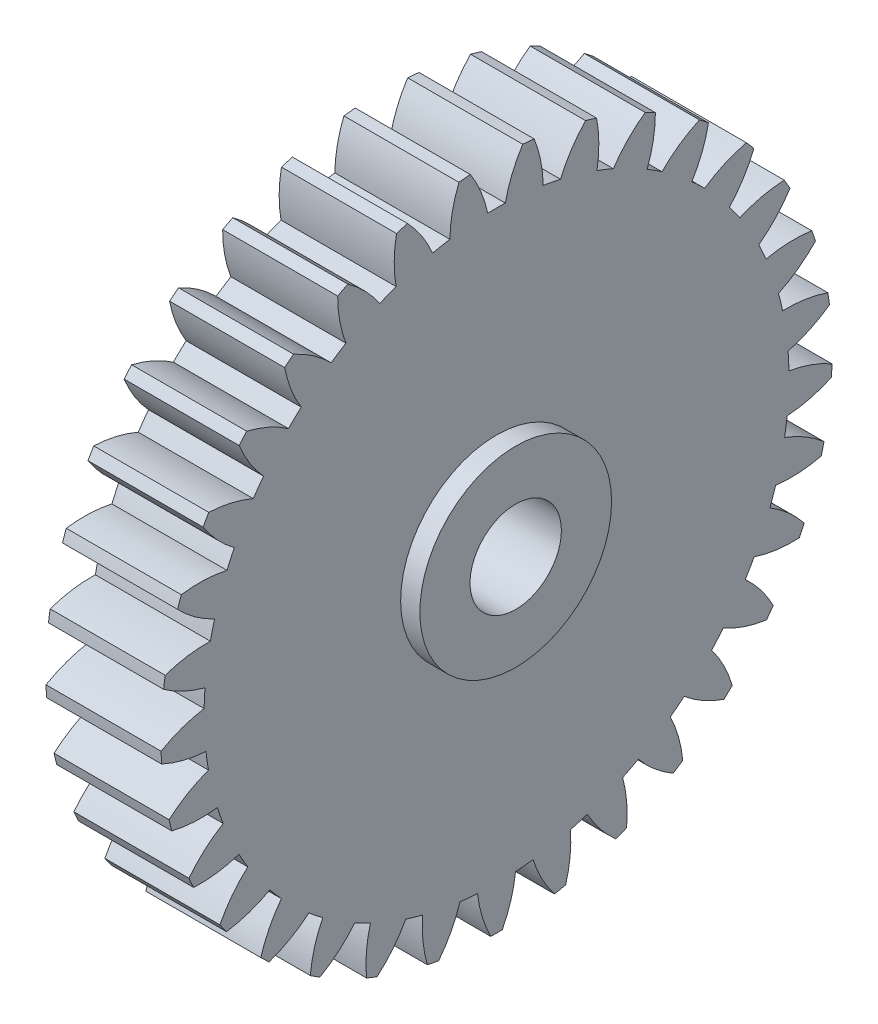
SolidWorks part; units mm, degrees
ref_plane "Plane1" through (0, 0, 0) normal (0, 0, 1) x (1, 0, 0)
ref_plane "Plane2" through (0, 0, 0) normal (0, 1, 0) x (1, 0, 0)
ref_plane "Plane3" through (0, 0, 0) normal (1, 0, 0) x (0, 0, -1)
sketch "HoldingSke" plane through (0, 0, 0) normal (0, 1, 0) x (1, 0, 0)
  line L0 (0, 0) -> (0.8387, -0.5446)
  line L1 (-15, 0) -> (100, 0) construction
  line L2 (0, 0) -> (-2.1039, 2.3779)
  line L3 (0, 0) -> (-11.863, 4.5341)
  line L4 (0, 0) -> (7.2428, 4.7035)
  line L5 (0, 0) -> (-46.8476, -17.4728)
  line L6 (0, 0) -> (-6.6317, -4.4744)
  line L7 (-2.1039, 2.3779) -> (8.6586, 51.2059)
  line L8 (-76.2, 54.61) -> (-74.4, 54.61)
  line L9 (-71.009, 38.7566) -> (-53.1078, 45.2721)
  line L10 (-76.2, 71.12) -> (104.1128, 71.12)
  line L11 (0, 0) -> (-8, 0)
  line L12 (-76.2, 101.6) -> (-76.162, 101.6)
  line L13 (24.9733, 27.94) -> (52.9518, 28.4284)
  line L14 (24.9733, 27.94) -> (24.9743, 27.94)
  line L15 (24.9733, 27.94) -> (100.4006, 29.5858)
  line L16 (-63.627, -1) -> (-12.827, -1)
  circle A0 centre (0, 0) radius 5
  circle A1 centre (0, 0) radius 15.249
  circle A2 centre (0, 0) radius 37.5
  circle A3 centre (0, 0) radius 5
  dimension "MHD" = 30.498
  dimension "Hub_dia" = 75
  dimension "Bore" = 10
  dimension "MBD" = 10
  dimension "Num_teeth" = 33
  dimension "Pitch" = 1
  dimension "Overall_len" = 50
  dimension "Show_teeth" = 33
  dimension "Thickness" = 8
  dimension "OAL" = 50.0001
  dimension "T_dim" = 1.8
  dimension "Ap" = 20
  dimension "H" = 19.05
  dimension "Pitch_radius" = 180.3128
  dimension "Width" = 8
  dimension "Backlash" = 0.038
  dimension "Addendum_fac" = 1
  dimension "Dedendum_fac" = 1.25
  dimension "Clearance_fac" = 0.25
  dimension "Dedendum_add" = 0.001
  dimension "Module" = 1
sketch "BasProSke" plane through (0, 0, 0) normal (0, 1, 0) x (1, 0, 0)
  line L0 (-10, 0) -> (60, 0) construction
  line L1 (0, 0) -> (0, 17.5)
  line L2 (0, 0) -> (6, 0)
  line L3 (6, 0) -> (6, 17.5)
  line L4 (6, 17.5) -> (0, 17.5)
  dimension "Thickness" = 6
  dimension "Diameter" = 35
revolve "Base-Revolve" add sketch "BasProSke" angle 360 about L0
sketch "TooCutSke" plane through (0, 0, 0) normal (1, 0, 0) x (0, 0, -1)
  line L1 (0, 0) -> (0, 107) construction
  line L2 (0, 0) -> (-0.8516, 16.478) construction
  line L3 (0, 0) -> (-3.1339, 32.8194) construction
  line L4 (-0.8516, 16.478) -> (-1.5669, 16.4097) construction
  arc A0 (0.46, 15.2421) -> (-0.46, 15.2421) centre (0, 0) ccw
  arc A1 (1.3819, 17.4708) -> (-1.3819, 17.4708) centre (0, 0) ccw
  circle A2 centre (0, 0) radius 16.5 construction
  circle A3 centre (0, 0) radius 15.5049 construction
  arc A4 (-0.46, 15.2421) -> (-1.3819, 17.4708) centre (-6.9172, 13.8764) ccw
  arc A5 (1.3819, 17.4708) -> (0.46, 15.2421) centre (6.9172, 13.8764) ccw
  dimension "Root_dia" = 30.498
  dimension "Overcut_dia" = 35.0508
  dimension "Pitch_dia" = 33
  dimension "Base_dia" = 31.0099
  dimension "Flank_rad" = 6.6
  dimension "Half_ang" = 5.455
  dimension "Half_CT" = 0.7186
extrude "ToothCut" cut sketch "TooCutSke" along normal through all
fillet "Breaks" [suppressed] radius 0.02
fillet "RootFillets" [suppressed] radius 0.251
pattern_circular "TeethCuts" count 33 every 10.909 about axis through (-10, 0, 0) along (1, 0, 0) of "ToothCut", "RootFillets", "Breaks"
sketch "HubNeaOneSke" plane through (0, 0, 0) normal (-1, 0, 0) x (0, 0, 1)
  circle A0 centre (0, 0) radius 15.249
  dimension "Diameter" = 30.498
extrude "HubNearOne" [suppressed] add sketch "HubNeaOneSke" along normal blind 44.0001
sketch "HubNeaBotSke" plane through (0, 0, 0) normal (-1, 0, 0) x (0, 0, 1)
  circle A0 centre (0, 0) radius 15.249
  dimension "Diameter" = 30.498
extrude "HubNearBoth" [suppressed] add sketch "HubNeaBotSke" along normal blind 22
ref_plane "FarPln" through (6, 0, 0) normal (1, 0, 0) x (0, 0, -1)
sketch "HubFarSke" plane through (6, 0, 0) normal (1, 0, 0) x (0, 0, -1)
  circle A0 centre (0, 0) radius 15.249
  dimension "Diameter" = 30.498
extrude "HubFar" [suppressed] add sketch "HubFarSke" along normal blind 22
sketch "BorSke" plane through (0, 0, 0) normal (1, 0, 0) x (0, 0, -1)
  circle A0 centre (0, 0) radius 5
  dimension "Diameter" = 10
extrude "Bore" cut sketch "BorSke" along normal mid plane 100.0001
sketch "KeySke" plane through (0, 0, 0) normal (1, 0, 0) x (0, 0, -1)
  line L0 (-2, 0) -> (-2, 6.8)
  line L1 (-2, 6.8) -> (2, 6.8)
  line L2 (2, 6.8) -> (2, 0)
  line L3 (0, 0) -> (0, 34) construction
  line L4 (-2, 0) -> (2, 0)
  dimension "Offset" = 6.8
  dimension "Width" = 4
extrude "Keyway" [suppressed] cut sketch "KeySke" along normal mid plane 100.0001
pattern_circular "Keyway2" [suppressed] count 2 every 90 about axis through (-10, 0, 0) along (1, 0, 0)
sketch "Croquis1" plane through (6, 0, 0) normal (1, 0, 0) x (0, 0, -1)
  circle A0 centre (0, 0) radius 5 construction
  circle A1 centre (0, 0) radius 5
  circle A2 centre (0, 0) radius 2.3812
  dimension "D1" = 4.7625
extrude "Saliente-Extruir2" add sketch "Croquis1" along normal blind 1 and the other way through all
equation "' \"Module@HoldingSke\" = 6.35"
equation "' \"Num_teeth@HoldingSke\" = 12"
equation "' \"Ap@HoldingSke\" =  20"
equation "' \"Ap@HoldingSke\" = 20"
equation "' \"Width@HoldingSke\" = 0.5 * 25.4"
equation "' \"Hub_dia@HoldingSke\"= 1 * 25.4"
equation "' \"Hub_dia@HoldingSke\" = 1 * 25.4"
equation "' \"Overall_len@HoldingSke\" = 1.0 * 25.4"
equation "' \"Bore@HoldingSke\" = 0.75 * 25.4"
equation "' \"T_dim@HoldingSke\" = 0.1 * 25.4"
equation "' \"Width@KeySke\" = 0.25 * 25.4"
equation "' \"Show_teeth@HoldingSke\" = 13"
equation "' \"Backlash@HoldingSke\" = 0.009 * 25.4"
equation "' \"Addendum_fac@HoldingSke\" = 1.0"
equation "' \"Dedendum_fac@HoldingSke\" = 1.25"
equation "' \"Dedendum_add@HoldingSke\" = 0.00005 * 25.4"
equation "' \"Clearance_fac@HoldingSke\" = 0.25"
equation "\"Pitch@HoldingSke\" = 1 / \"Module@HoldingSke\""
equation "\"Overcut_dia@TooCutSke\" = (\"Num_teeth@HoldingSke\" + 2 * \"Addendum_fac@HoldingSke\") / \"Pitch@HoldingSke\" + 0.002 * 25.4"
equation "\"Pitch_dia@TooCutSke\" = \"Num_teeth@HoldingSke\" / \"Pitch@HoldingSke\""
equation "\"Base_dia@TooCutSke\" = \"Num_teeth@HoldingSke\" / \"Pitch@HoldingSke\" * cos((\"Ap@HoldingSke\"  * 3.14159265 / 180))"
equation "\"Root_dia@TooCutSke\" = (\"Num_teeth@HoldingSke\" + 2) / \"Pitch@HoldingSke\" - 2 * (\"Addendum_fac@HoldingSke\" + \"Dedendum_fac@HoldingSke\") / \"Pitch@HoldingSke\" - \"Dedendum_add@HoldingSke\" * 2"
equation "\"Half_ang@TooCutSke\" = 180 / \"Num_teeth@HoldingSke\""
equation "\"Half_CT@TooCutSke\" = \"Num_teeth@HoldingSke\" / \"Pitch@HoldingSke\" * sin((3.14159265 / 2 / \"Num_teeth@HoldingSke\")) / 2 - 7 * \"Backlash@HoldingSke\" / 4"
equation "\"Flank_rad@TooCutSke\" = \"Num_teeth@HoldingSke\" / \"Pitch@HoldingSke\" / 5"
equation "\"Radius@RootFillets\" = \"Clearance_fac@HoldingSke\" / \"Pitch@HoldingSke\" + \"Dedendum_add@HoldingSke\""
equation "\"Break_rad@Breaks\" = 0.02 / \"Pitch@HoldingSke\""
equation "\"Thickness@HoldingSke\" = \"Width@HoldingSke\""
equation "\"OAL@HoldingSke\" = \"Thickness@HoldingSke\""
equation "\"MHD@HoldingSke\" = (\"Num_teeth@HoldingSke\" + 2) / \"Pitch@HoldingSke\" - 2 * (\"Addendum_fac@HoldingSke\" + \"Dedendum_fac@HoldingSke\")  / \"Pitch@HoldingSke\" - \"Dedendum_add@HoldingSke\" * 2"
equation "\"MBD@HoldingSke\" = (\"Num_teeth@HoldingSke\" + 2) / \"Pitch@HoldingSke\" - 2 * (\"Addendum_fac@HoldingSke\" + \"Dedendum_fac@HoldingSke\")  / \"Pitch@HoldingSke\" - \"Dedendum_add@HoldingSke\" * 2 - 0.002 * 25.4"
equation "\"MHD@HoldingSke\" = ((sgn( \"MHD@HoldingSke\" - \"Hub_dia@HoldingSke\" )-1)*( \"MHD@HoldingSke\" - \"Hub_dia@HoldingSke\" ))/-2+ \"Hub_dia@HoldingSke\""
equation "\"MBD@HoldingSke\" = ((sgn( \"MBD@HoldingSke\" - \"Bore@HoldingSke\" )-1)*( \"MBD@HoldingSke\" - \"Bore@HoldingSke\" ))/-2+ \"Bore@HoldingSke\""
equation "\"OAL@HoldingSke\" = ((sgn( \"OAL@HoldingSke\" - \"Overall_len@HoldingSke\" )+1)*( \"OAL@HoldingSke\" - \"Overall_len@HoldingSke\" ))/2 + \"Overall_len@HoldingSke\" + 0.000002 * 25.4"
equation "\"Num_teeth@TeethCuts\" = int( \"Show_teeth@HoldingSke\" ) + 1"
equation "\"Num_teeth@TeethCuts\" = ((sgn( \"Num_teeth@TeethCuts\" - \"Num_teeth@HoldingSke\" )-1)*( \"Num_teeth@TeethCuts\" - \"Num_teeth@HoldingSke\" ))/-2+ \"Num_teeth@HoldingSke\""
equation "\"Num_teeth@TeethCuts\" = ((sgn( \"Num_teeth@TeethCuts\" - 2.0)+1)*( \"Num_teeth@TeethCuts\" - 2.0))/2 +2.0"
equation "\"Angle@TeethCuts\" = 360.0 / \"Num_teeth@HoldingSke\""
equation "\"Diameter@BasProSke\" = (\"Num_teeth@HoldingSke\" + 2 * \"Addendum_fac@HoldingSke\") / \"Pitch@HoldingSke\""
equation "' \"Fillet_rad@BasProSke\" =  \"Thickness@HoldingSke\" * 0.05"
equation "' \"Fillet_rad@BasProSke\" = \"Thickness@HoldingSke\" * 0.05"
equation "\"MHD@HoldingSke\" = ((sgn( \"MHD@HoldingSke\" - \"Root_dia@TooCutSke\" )-1)*( \"MHD@HoldingSke\" - \"Root_dia@TooCutSke\" ))/-2+ \"Root_dia@TooCutSke\""
equation "\"Diameter@HubNeaOneSke\" = \"MHD@HoldingSke\""
equation "\"Length@HubNearOne\" = \"OAL@HoldingSke\" - \"Thickness@BasProSke\""
equation "\"Diameter@HubNeaBotSke\" = \"MHD@HoldingSke\""
equation "\"Length@HubNearBoth\" = ( \"OAL@HoldingSke\" - \"Thickness@BasProSke\" ) / 2.0"
equation "\"Thickness@FarPln\" = \"Thickness@BasProSke\""
equation "\"Diameter@HubFarSke\" = \"MHD@HoldingSke\""
equation "\"Length@HubFar\" = ( \"OAL@HoldingSke\" - \"Thickness@BasProSke\" ) / 2.0"
equation "\"Diameter@BorSke\" = \"MBD@HoldingSke\""
equation "\"D1@Bore\" = \"OAL@HoldingSke\" * 2.0"
equation "\"D1@Keyway\" = \"OAL@HoldingSke\" * 2.0"
equation "\"Offset@KeySke\" = \"T_dim@HoldingSke\" + \"MBD@HoldingSke\" / 2.0"
